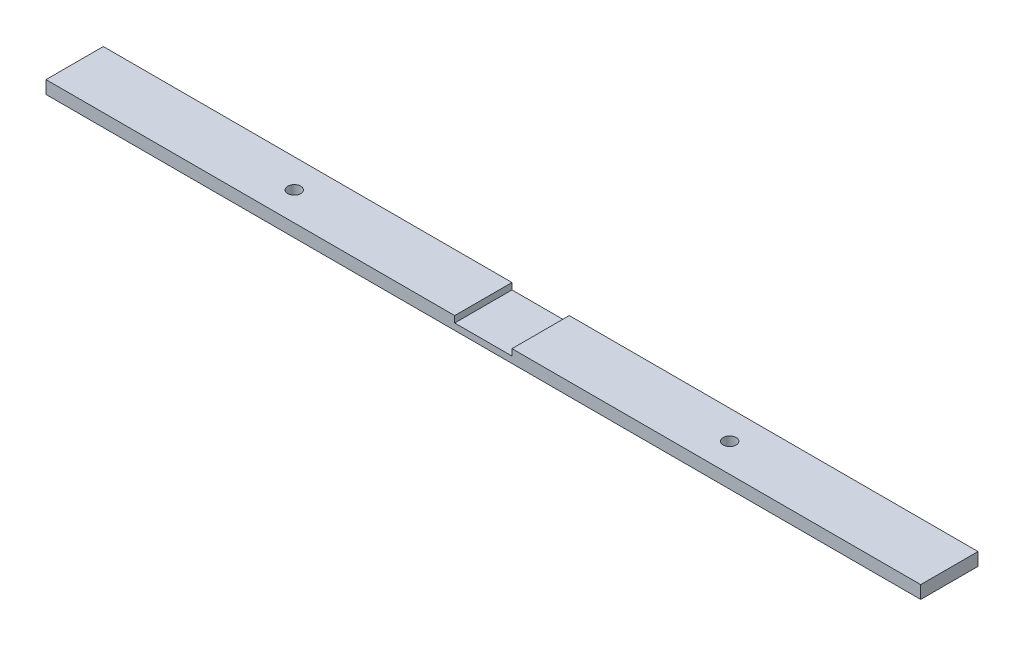
SolidWorks part; units mm, degrees
material "Polyetheretherketone (PEEK)"
ref_plane "Front Plane" through (0, 0, 0) normal (0, 0, 1) x (1, 0, 0)
ref_plane "Top Plane" through (0, 0, 0) normal (0, 1, 0) x (1, 0, 0)
ref_plane "Right Plane" through (0, 0, 0) normal (1, 0, 0) x (0, 0, -1)
sketch "Sketch1" plane through (0, 0, 0) normal (0, 1, 0) x (1, 0, 0)
  line L0 (-57, 0) -> (57, 0) construction
  line L1 (-114.5, -7.5) -> (114.5, -7.5)
  line L2 (-114.5, -7.5) -> (-114.5, 7.5)
  line L3 (-114.5, 7.5) -> (114.5, 7.5)
  line L4 (114.5, -7.5) -> (114.5, 7.5)
  line L5 (-114.5, -7.5) -> (114.5, 7.5) construction
  line L6 (-114.5, 7.5) -> (114.5, -7.5) construction
  point P0 (0, 0)
  dimension "D1" = 229
  dimension "D2" = 15
  dimension "D3" = 57.5
extrude "Boss-Extrude1" add sketch "Sketch1" along normal blind 3.375
sketch "Sketch7" plane through (0, 0, 0) normal (0, -1, 0) x (1, 0, 0)
  line L0 (-57, 0) -> (57, 0) construction
  line L1 (-57, 0) -> (57, 0)
hole_wizard "M3 Clearance Hole1" positions "Sketch8" profile "Sketch9" hole size "M3" standard "ANSI Metric" end condition through all
sketch "Sketch8" plane through (0, 0, 0) normal (0, -1, 0) x (-1, 0, 0)
  point P0 (57, 0)
  point P3 (-57, 0)
sketch "Sketch9" plane through (-57, 0, 0) normal (1, 0, 0) x (0, 0, -1)
  line L0 (0, 0) -> (0, 3.375)
  line L1 (0, 3.375) -> (1.7, 3.375)
  line L2 (1.7, 3.375) -> (1.7, 0)
  line L5 (1.7, 0) -> (0, 0)
  line L11 (0, -6.35) -> (0, 107.95) construction
  dimension "Thru Hole Dia." = 3.4
  dimension "Thru Hole Depth" = 3.375
sketch "Sketch10" plane through (0, 0, 7.5) normal (0, 0, 1) x (1, 0, 0)
  line L0 (0, 0) -> (0, 3.375) construction
  line L1 (-114.5, 0) -> (114.5, 0) construction
  line L2 (-114.5, 3.375) -> (114.5, 3.375) construction
  line L3 (-7.5, 1.6875) -> (7.5, 1.6875)
  line L4 (-7.5, 1.6875) -> (-7.5, 3.375)
  line L5 (-7.5, 3.375) -> (7.5, 3.375)
  line L6 (7.5, 3.375) -> (7.5, 1.6875)
  point P6 (0, 1.6875)
  dimension "D1" = 15
extrude "Cut-Extrude1" cut sketch "Sketch10" against normal through all both and the other way through all
